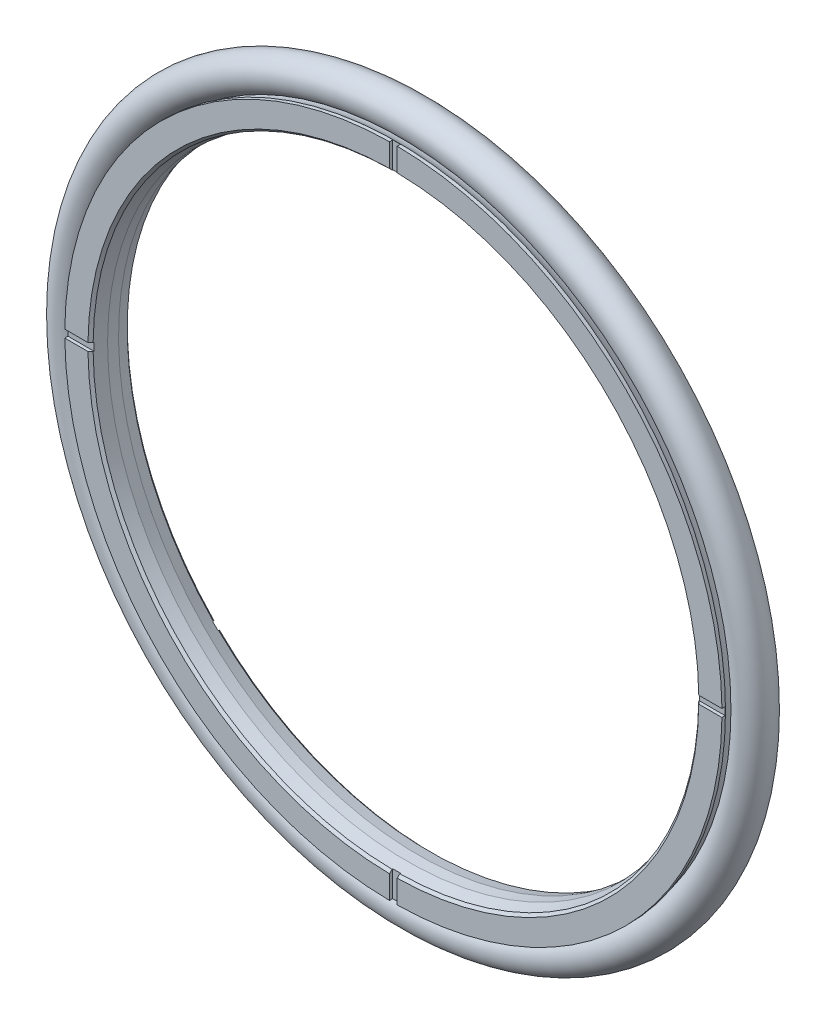
SolidWorks part; units mm, degrees
material "PTFE+NBR"
ref_plane "Front Plane" through (0, 0, 0) normal (0, 0, 1) x (1, 0, 0)
ref_plane "Top Plane" through (0, 0, 0) normal (0, 1, 0) x (1, 0, 0)
ref_plane "Right Plane" through (0, 0, 0) normal (1, 0, 0) x (0, 0, -1)
sketch "Sketch1" plane through (0, 0, 0) normal (1, 0, 0) x (0, 0, -1)
  line L0 (0, 0) -> (45.3047, 0) construction
  line L1 (0, 0) -> (0, 68.4894) construction
  line L2 (-3.05, 51.05) -> (-3.05, 47.45)
  line L3 (-0.85, 46.6) -> (0.85, 46.6)
  line L4 (3.05, 47.45) -> (3.05, 51.05)
  line L5 (-10.6026, 41.25) -> (12.2584, 41.25) construction
  line L6 (-3.05, 51.05) -> (-2.4995, 51.05)
  line L7 (3.05, 51.05) -> (2.4995, 51.05)
  line L8 (-2.65, 47.05) -> (-0.85, 46.6)
  line L9 (2.65, 47.05) -> (0.85, 46.6)
  line L10 (2.65, 47.05) -> (3.05, 47.45)
  line L11 (-3.05, 47.45) -> (-2.65, 47.05)
  arc A1 (-2.4995, 51.05) -> (2.4995, 51.05) centre (0, 53.5) ccw
  point P11 (-3.05, 47.15)
  point P15 (3.05, 47.15)
  dimension "D4" = 3.5
  dimension "D5" = 4.45
  dimension "D6" = 100
  dimension "D1" = 93.2
  dimension "D2" = 6.1
  dimension "D3" = 41.25
  dimension "D7" = 2.2
  dimension "D8" = 4
  dimension "D9" = 3.6
  dimension "D10" = 45
  dimension "D11" = 0.3
  dimension "D12" = 45
  dimension "D13" = 0.5505
  dimension "D14" = 94.9
  dimension "D15" = 102.1
revolve "Revolve1" add sketch "Sketch1" angle 360 about L0
sketch "Sketch3" plane through (0, 0, 3.05) normal (0, 0, 1) x (1, 0, 0)
  line L0 (0, 0) -> (0, 42.9701) construction
  line L2 (-0.6, 54.5677) -> (0.6, 54.5677)
  line L3 (-0.6, 54.5677) -> (-0.6, 0)
  line L4 (-0.6, 0) -> (0.6, 0)
  line L5 (0.6, 54.5677) -> (0.6, 0)
  dimension "D1" = 1.2
  dimension "D2" = 54.5677
extrude "Cut-Extrude1" cut sketch "Sketch3" against normal blind 0.5
sketch "Sketch4" plane through (0, 0, -3.05) normal (0, 0, -1) x (-1, 0, 0)
  line L0 (0, 0) -> (30.7412, 30.7412) construction
  line L1 (0, 0) -> (54.0122, 0) construction
  line L2 (0.4243, -0.4243) -> (-0.4243, 0.4243)
  line L3 (-0.4243, 0.4243) -> (46.107, 46.9556)
  line L4 (46.107, 46.9556) -> (46.9556, 46.107)
  line L5 (0.4243, -0.4243) -> (46.9556, 46.107)
  point P9 (46.5313, 46.5313)
  dimension "D1" = 45
  dimension "D2" = 1.2
  dimension "D3" = 65.8052
extrude "Cut-Extrude2" cut sketch "Sketch4" against normal blind 0.5
pattern_circular "CirPattern1" count 4 over 360 of "Cut-Extrude1", "Cut-Extrude2"
sketch "Sketch2" plane through (0, 0, 0) normal (1, 0, 0) x (0, 0, -1)
  line L0 (0, 0) -> (20.1543, 0) construction
  circle A0 centre (0, 53.165) radius 2.665
  dimension "D1" = 5.33
  dimension "D2" = 101
revolve "Revolve2" add sketch "Sketch2" angle 360 about L0
